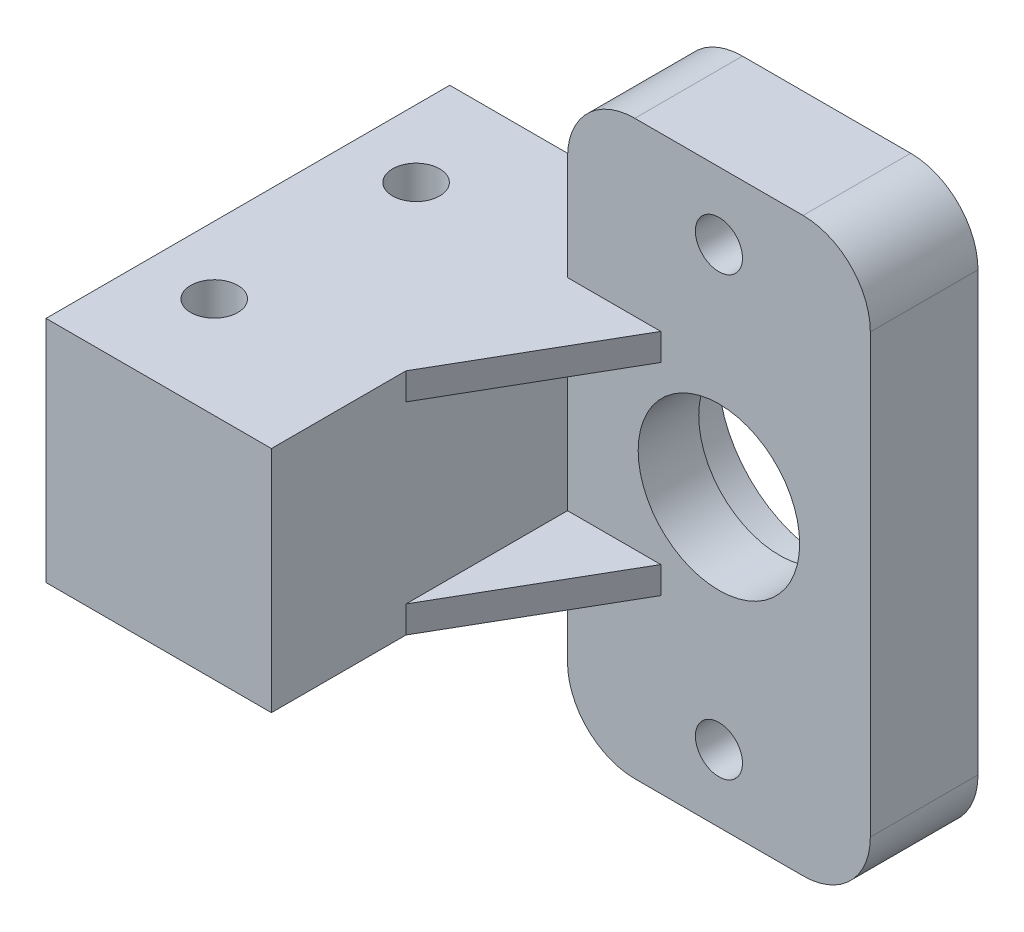
SolidWorks part; units mm, degrees
ref_plane "前视基准面" through (0, 0, 0) normal (0, 0, 1) x (1, 0, 0)
ref_plane "上视基准面" through (0, 0, 0) normal (0, 1, 0) x (1, 0, 0)
ref_plane "右视基准面" through (0, 0, 0) normal (1, 0, 0) x (0, 0, -1)
sketch "草图1" plane through (0, 0, 0) normal (0, 0, 1) x (1, 0, 0)
  line B0 (-28, 8.5) -> (-28, -8.5)
  line B1 (-11.25, 16.25) -> (-11.25, -16.25)
  line B2 (11.25, 16.25) -> (11.25, -16.25)
  line B3 (-28, 8.5) -> (-11.25, 8.5)
  line B4 (-28, -8.5) -> (-11.25, -8.5)
  line B5 (-6.25, 21.25) -> (6.25, 21.25)
  line B6 (-6.25, -21.25) -> (6.25, -21.25)
  line B7 (-23, 8.5) -> (-23, -8.5)
  circle B8 centre (0, 16.25) radius 1.75
  arc B9 (-6.25, 21.25) -> (-11.25, 16.25) centre (-6.25, 16.25) ccw
  arc B10 (11.25, 16.25) -> (6.25, 21.25) centre (6.25, 16.25) ccw
  circle B11 centre (0, 0) radius 6
  circle B12 centre (0, 0) radius 8.05
  circle B13 centre (0, -16.25) radius 1.75
  arc B14 (-11.25, -16.25) -> (-6.25, -21.25) centre (-6.25, -16.25) ccw
  arc B15 (6.25, -21.25) -> (11.25, -16.25) centre (6.25, -16.25) ccw
sketch_block_instance "块1-1"
sketch_block "块1"
sketch "草图2" plane through (0, 0, 0) normal (0, 0, 1) x (1, 0, 0)
  line L0 (-6.25, 21.25) -> (6.25, 21.25) construction
  line L1 (11.25, 16.25) -> (11.25, -16.25) construction
  line L2 (-6.25, -21.25) -> (6.25, -21.25) construction
  line L3 (-11.25, 16.25) -> (-11.25, -16.25) construction
  line L4 (-6.25, 21.25) -> (6.25, 21.25)
  line L5 (11.25, 16.25) -> (11.25, -16.25)
  line L6 (-6.25, -21.25) -> (6.25, -21.25)
  line L7 (-11.25, 16.25) -> (-11.25, -16.25)
  arc A0 (11.25, 16.25) -> (6.25, 21.25) centre (6.25, 16.25) ccw construction
  arc A1 (6.25, -21.25) -> (11.25, -16.25) centre (6.25, -16.25) ccw construction
  arc A2 (-11.25, -16.25) -> (-6.25, -21.25) centre (-6.25, -16.25) ccw construction
  arc A3 (-6.25, 21.25) -> (-11.25, 16.25) centre (-6.25, 16.25) ccw construction
  circle A4 centre (0, -16.25) radius 1.75 construction
  circle A5 centre (0, 0) radius 6 construction
  arc A6 (11.25, 16.25) -> (6.25, 21.25) centre (6.25, 16.25) ccw
  arc A7 (6.25, -21.25) -> (11.25, -16.25) centre (6.25, -16.25) ccw
  arc A8 (-11.25, -16.25) -> (-6.25, -21.25) centre (-6.25, -16.25) ccw
  arc A9 (-6.25, 21.25) -> (-11.25, 16.25) centre (-6.25, 16.25) ccw
  circle A10 centre (0, -16.25) radius 1.75
  circle A11 centre (0, 0) radius 6
  circle A12 centre (0, 16.25) radius 1.75 construction
  circle A13 centre (0, 16.25) radius 1.75
extrude "凸台-拉伸1" add sketch "草图2" along normal blind 8
sketch "草图3" plane through (0, 0, 0) normal (0, 0, -1) x (-1, 0, 0)
  circle A0 centre (0, 0) radius 8.05 construction
  circle A1 centre (0, 0) radius 8.05
extrude "切除-拉伸1" cut sketch "草图3" against normal blind 3.5
sketch "草图4" plane through (0, 0, 0) normal (0, 0, 1) x (1, 0, 0)
  line L0 (-28, 8.5) -> (-11.25, 8.5) construction
  line L1 (-28, 8.5) -> (-28, -8.5) construction
  line L2 (-28, -8.5) -> (-11.25, -8.5) construction
  line L3 (-11.25, 16.25) -> (-11.25, -16.25) construction
  line L4 (-28, 8.5) -> (-11.25, 8.5)
  line L5 (-28, 8.5) -> (-28, -8.5)
  line L6 (-28, -8.5) -> (-11.25, -8.5)
  line L7 (-11.25, 8.5) -> (-11.25, -8.5)
extrude "凸台-拉伸2" add sketch "草图4" along normal blind 30
sketch "草图5" plane through (0, -8.5, 0) normal (0, -1, 0) x (1, 0, 0)
  line L0 (-28, 30) -> (-28, 0) construction
  line L1 (-28, 30) -> (-11.25, 30) construction
  line L2 (-28, 0) -> (-11.25, 0) construction
  circle A0 centre (-23, 22.5) radius 1.75
  circle A1 centre (-23, 7.5) radius 1.75
  dimension "D4" = 3.5
  dimension "D1" = 5
  dimension "D2" = 7.5
  dimension "D3" = 7.5
extrude "切除-拉伸2" cut sketch "草图5" against normal through all
sketch "草图7" plane through (0, -8.5, 0) normal (0, -1, 0) x (1, 0, 0)
  line L0 (-11.25, 20) -> (-11.25, 8)
  line L1 (-11.25, 30) -> (-11.25, 8) construction
  line L2 (-11.25, 8) -> (-4.3218, 8)
  line L3 (-6.25, 8) -> (6.25, 8) construction
  line L4 (-4.3218, 8) -> (-11.25, 20)
  dimension "D1" = 60
  dimension "D2" = 12
extrude "凸台-拉伸3" add sketch "草图7" against normal blind 2
sketch "草图8" plane through (0, 8.5, 0) normal (0, 1, 0) x (1, 0, 0)
  line L0 (-4.3218, -8) -> (-11.25, -20) construction
  line L1 (-11.25, -8) -> (-4.3218, -8) construction
  line L2 (-11.25, -20) -> (-11.25, -8) construction
  line L3 (-4.3218, -8) -> (-11.25, -20)
  line L4 (-11.25, -8) -> (-4.3218, -8)
  line L5 (-11.25, -20) -> (-11.25, -8)
extrude "凸台-拉伸4" add sketch "草图8" against normal blind 2
